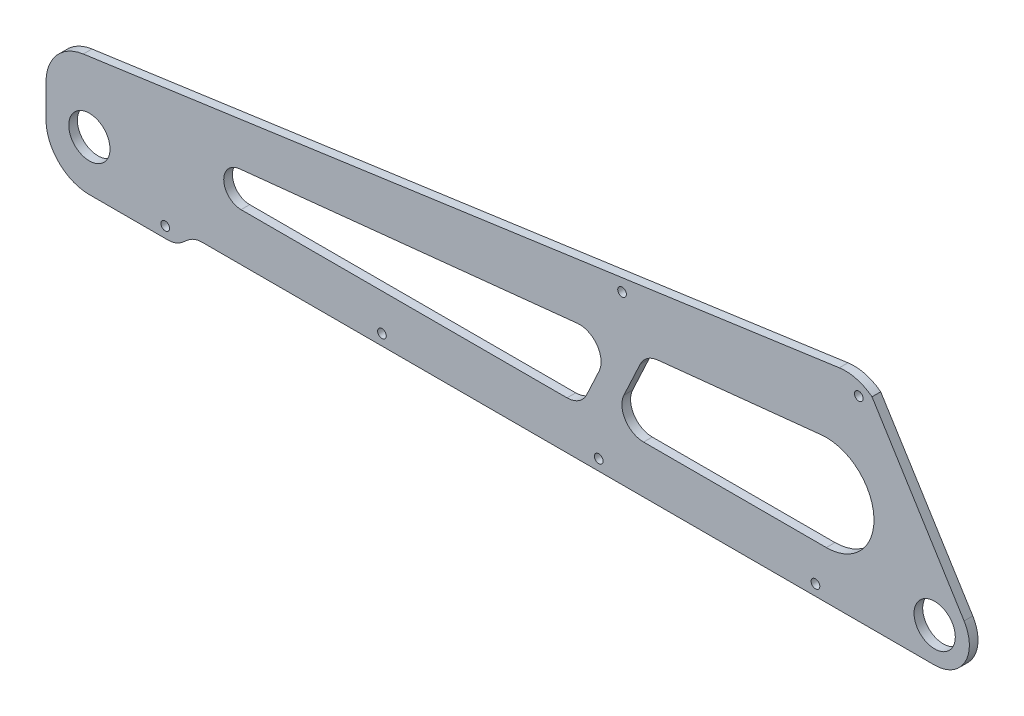
SolidWorks part; units mm, degrees
ref_plane "前视基准面" through (0, 0, 0) normal (0, 0, 1) x (1, 0, 0)
ref_plane "上视基准面" through (0, 0, 0) normal (0, 1, 0) x (1, 0, 0)
ref_plane "右视基准面" through (0, 0, 0) normal (1, 0, 0) x (0, 0, -1)
sketch "草图1" plane through (0, 0, 0) normal (0, 0, 1) x (1, 0, 0)
  line L0 (40.9883, -22.5717) -> (125.2914, -22.5717)
  line L1 (123.0161, 21.3103) -> (47.4514, 13.4528)
  line L2 (39.4226, 7.7326) -> (31.9252, -8.3456)
  line L3 (-144.7086, -22.5717) -> (5.6802, -22.5717)
  line L4 (14.7433, -16.7979) -> (20.4414, -4.5783)
  line L5 (10.344, 9.5943) -> (-145.536, -6.6146)
  line L6 (-217.492, 3.2336) -> (131.2874, 52.2514)
  line L8 (-169.1545, -46.9113) -> (-171.9204, -49.2322)
  line L9 (-178.3483, -51.5717) -> (-214.7086, -51.5717)
  line L10 (-234.7086, -31.5717) -> (-234.7086, -16.5717)
  line L13 (-162.7266, -44.5717) -> (175.2914, -44.5717)
  line L14 (146.3841, 48.2062) -> (188.8782, -20.122)
  circle A1 centre (120.2914, -39.5717) radius 2
  circle A2 centre (31.0623, 32.4283) radius 2
  circle A3 centre (175.2914, -28.5717) radius 9.52
  circle A4 centre (-79.7086, -39.5717) radius 2
  circle A5 centre (-214.7086, -28.5717) radius 9.52
  circle A6 centre (140.2914, 45.4283) radius 2
  circle A7 centre (-179.7086, -46.5717) radius 2
  circle A8 centre (20.2914, -39.5717) radius 2
  arc A9 (125.2914, -22.5717) -> (123.0161, 21.3103) centre (125.2914, -0.5717) ccw
  arc A10 (47.4514, 13.4528) -> (39.4226, 7.7326) centre (48.4857, 3.5064) ccw
  arc A11 (31.9252, -8.3456) -> (40.9883, -22.5717) centre (40.9883, -12.5717) ccw
  arc A12 (-145.536, -6.6146) -> (-144.7086, -22.5717) centre (-144.7086, -14.5717) ccw
  arc A13 (5.6802, -22.5717) -> (14.7433, -16.7979) centre (5.6802, -12.5717) ccw
  arc A14 (20.4414, -4.5783) -> (10.344, 9.5943) centre (11.3783, -0.3521) ccw
  arc A15 (-217.492, 3.2336) -> (-234.7086, -16.5717) centre (-214.7086, -16.5717) ccw
  arc A16 (146.3841, 48.2062) -> (131.2874, 52.2514) centre (134.0709, 32.446) ccw
  arc A18 (-162.7266, -44.5717) -> (-169.1545, -46.9113) centre (-162.7266, -54.5717) ccw
  arc A19 (-178.3483, -51.5717) -> (-171.9204, -49.2322) centre (-178.3483, -41.5717) ccw
  arc A20 (-234.7086, -31.5717) -> (-214.7086, -51.5717) centre (-214.7086, -31.5717) ccw
  circle A21 centre (175.2914, -28.5717) radius 16 construction
  arc A22 (175.2914, -44.5717) -> (188.8782, -20.122) centre (175.2914, -28.5717) ccw
extrude "凸台-拉伸1" add sketch "草图1" along normal blind 4 contours L6 A16 L14 A22 L13 A18 L8 A19 L9 A20 L10 A15
